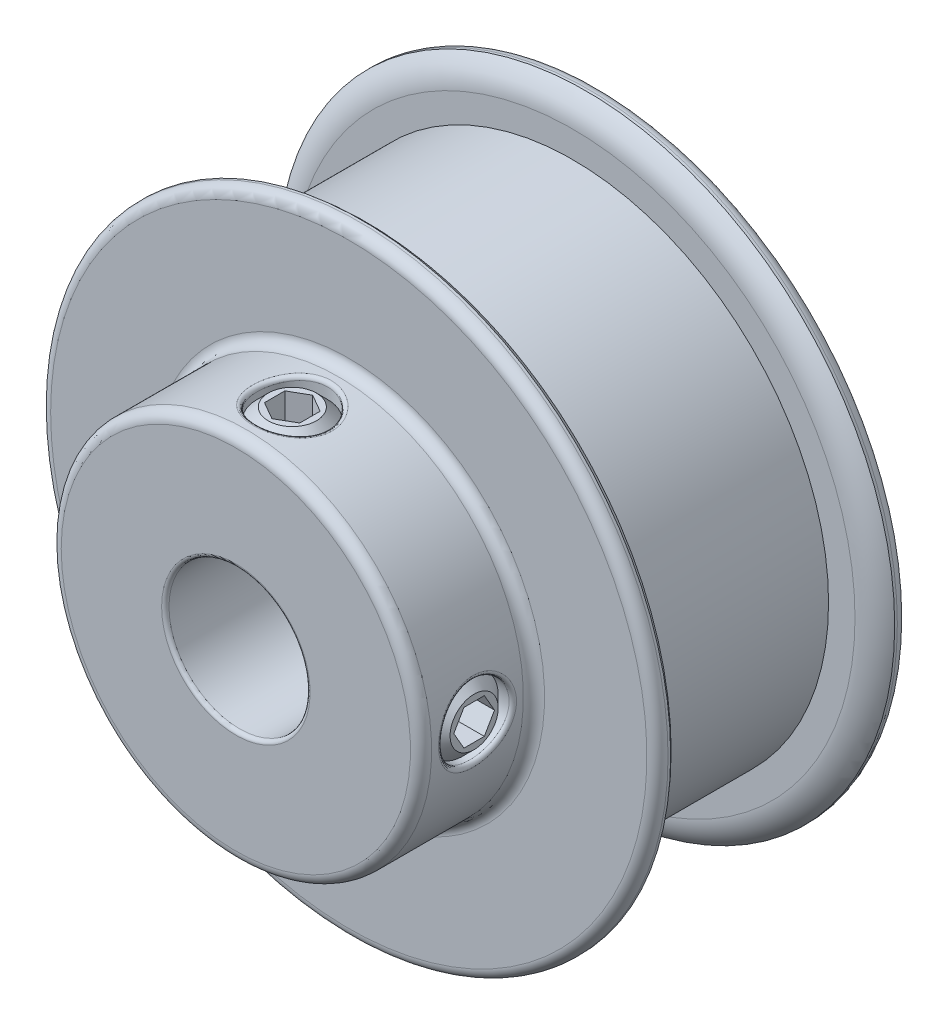
SolidWorks part; units mm, degrees
ref_plane "Front Plane" through (0, 0, 0) normal (0, 0, 1) x (1, 0, 0)
ref_plane "Top Plane" through (0, 0, 0) normal (0, 1, 0) x (1, 0, 0)
ref_plane "Right Plane" through (0, 0, 0) normal (1, 0, 0) x (0, 0, -1)
sketch "Sketch1" plane through (0, 0, 0) normal (0, 0, 1) x (1, 0, 0)
  line L0 (-1.2827, 14.4434) -> (-0.6905, 13.1734)
  line L1 (-0.6905, 13.1734) -> (0.6905, 13.1734)
  line L2 (0.6905, 13.1734) -> (1.2827, 14.4434)
  line L3 (-1.2827, 14.4434) -> (1.2827, 14.4434)
  line L4 (0, 0) -> (0, 13.1734) construction
  line L5 (0, 13.1734) -> (0, 15.4594) construction
  circle A0 centre (0, 0) radius 14.55 construction
  circle A1 centre (0, 0) radius 17.5 construction
  circle A2 centre (0, 0) radius 14.5002 construction
  point P6 (0, 14.4434)
  point P11 (0, 14.55)
  point P13 (0, 17.5)
  point P14 (0, 14.5002)
  dimension "Pitch Diameter" = 29.1
  dimension "OD" = 35
  dimension "D5" = 50
  dimension "D6" = 2.5654
  dimension "D4" = 1.27
  dimension "D3" = 2.286
  dimension "D2" = 0.9094
sketch "Sketch2" plane through (0, 0, 0) normal (1, 0, 0) x (0, 0, -1)
  line L0 (-10.3, 4) -> (10.3, 4) construction
  line L1 (-10.3, 4) -> (-10.3, 10.5) construction
  line L2 (-10.3, 10.5) -> (-3.9, 10.5) construction
  line L3 (-3.9, 10.5) -> (-3.9, 17.5) construction
  line L4 (-3.9, 17.5) -> (-2.4, 17.5) construction
  line L5 (-2.4, 17.5) -> (-2.4, 14.5002) construction
  line L6 (-2.4, 14.5002) -> (8.8, 14.5002) construction
  line L7 (8.8, 14.5002) -> (8.8, 17.5) construction
  line L8 (8.8, 17.5) -> (10.3, 17.5) construction
  line L9 (10.3, 17.5) -> (10.3, 4) construction
  line L10 (-10.3, 0) -> (10.3, 0) construction
  line L13 (-3.9, 17.5) -> (-3.15, 17.5) construction
  line L14 (-2.4, 16.0001) -> (-2.4, 14.5002) construction
  line L15 (8.8, 14.5002) -> (8.8, 16.0001) construction
  line L16 (9.55, 17.5) -> (10.3, 17.5) construction
  arc A0 (-2.4, 16.0001) -> (-3.15, 17.5) centre (-4.2748, 16.0001) ccw construction
  arc A1 (8.8, 16.0001) -> (9.55, 17.5) centre (10.6748, 16.0001) cw construction
  point P12 (-2.4, 16.0001)
  point P14 (-3.15, 17.5)
  point P20 (8.8, 16.0001)
  point P21 (9.55, 17.5)
  point P25 (8.8, 0)
  point P26 (-2.4, 0)
  dimension "Overall Width" = 20.6
  dimension "Outside Width" = 14.2
  dimension "Inside Width" = 11.2
  dimension "Hub Diameter" = 21
  dimension "For Shaft Diameter" = 8
sketch "Sketch7" plane through (0, 0, 0) normal (1, 0, 0) x (0, 0, -1)
  line L0 (-10.3, 4) -> (-10.3, 10.5) construction
  line L1 (-10.3, 10.5) -> (-3.9, 10.5) construction
  line L2 (-3.9, 10.5) -> (-3.9, 17.5) construction
  line L3 (-3.9, 17.5) -> (-3.15, 17.5) construction
  line L4 (-2.4, 16.0001) -> (-2.4, 14.5002) construction
  line L5 (-2.4, 14.5002) -> (8.8, 14.5002) construction
  line L6 (8.8, 14.5002) -> (8.8, 16.0001) construction
  line L7 (9.55, 17.5) -> (10.3, 17.5) construction
  line L8 (10.3, 17.5) -> (10.3, 4) construction
  line L9 (-10.3, 4) -> (10.3, 4) construction
  line L10 (-10.3, 4) -> (-10.3, 10.5)
  line L11 (-10.3, 10.5) -> (-3.9, 10.5)
  line L12 (-3.9, 10.5) -> (-3.9, 17.5)
  line L13 (-3.9, 17.5) -> (-3.15, 17.5)
  line L14 (-2.4, 16.0001) -> (-2.4, 14.5002)
  line L15 (-2.4, 14.5002) -> (8.8, 14.5002)
  line L16 (8.8, 14.5002) -> (8.8, 16.0001)
  line L17 (9.55, 17.5) -> (10.3, 17.5)
  line L18 (10.3, 17.5) -> (10.3, 4)
  line L19 (-10.3, 4) -> (10.3, 4)
  arc A0 (-2.4, 16.0001) -> (-3.15, 17.5) centre (-4.2748, 16.0001) ccw construction
  arc A1 (9.55, 17.5) -> (8.8, 16.0001) centre (10.6748, 16.0001) ccw construction
  arc A2 (-2.4, 16.0001) -> (-3.15, 17.5) centre (-4.2748, 16.0001) ccw
  arc A3 (9.55, 17.5) -> (8.8, 16.0001) centre (10.6748, 16.0001) ccw
revolve "Revolve1" add sketch "Sketch7" angle 360 about L10
sketch "Sketch4" plane through (0, 0, 0) normal (0, 1, 0) x (1, 0, 0)
  line L0 (0, -3.9) -> (0, -10.3) construction
  line L3 (0, -10.3) -> (0, 10.3) construction
  line L4 (-10.5, -3.9) -> (10.5, -3.9) construction
  line L5 (-10.5, -10.3) -> (10.5, -10.3) construction
  circle A0 centre (0, -7.1) radius 2
  dimension "D1" = 4
extrude "Cut-Extrude2" cut sketch "Sketch4" along normal through all
ref_plane "Plane1" through (0, 0, 7.1) normal (0, 0, 1) x (1, 0, 0)
sketch "Sketch5" plane through (0, 0, 7.1) normal (0, 0, 1) x (1, 0, 0)
  line L0 (0, 0) -> (0, 10.5) construction
  line L1 (-2, 10.3078) -> (-2, 3.4641) construction
  line L2 (-2, 10.3078) -> (-2, 3.4641) construction
  line L3 (0, 10.3078) -> (0, 4)
  line L4 (0, 4) -> (-1.365, 4)
  line L5 (-2, 9.6728) -> (-2, 4.635)
  line L6 (-1.365, 10.3078) -> (0, 10.3078)
  line L7 (-2, 9.6728) -> (-1.365, 10.3078)
  line L8 (-2, 4.635) -> (-1.365, 4)
  line L9 (0, 17.5) -> (0, 4) construction
  line L10 (0, 4) -> (0, 10.5) construction
  point P13 (-2, 4)
  point P15 (-2, 10.3078)
revolve "Revolve2" add sketch "Sketch5" angle 360 mid plane about L0
sketch "Sketch6" plane through (0, 10.3078, 0) normal (0, -1, 0) x (-1, 0, 0)
  line L1 (0, -5.9453) -> (-1, -6.5226)
  line L2 (-1, -6.5226) -> (-1, -7.6774)
  line L3 (-1, -7.6774) -> (0, -8.2547)
  line L4 (0, -8.2547) -> (1, -7.6774)
  line L5 (1, -7.6774) -> (1, -6.5226)
  line L6 (1, -6.5226) -> (0, -5.9453)
  circle A0 centre (0, -7.1) radius 1 construction
  dimension "D1" = 2
extrude "Cut-Extrude3" cut sketch "Sketch6" along normal blind 1.5
pattern_circular "CirPattern2" count 2 every 90 about axis through (0, 0, 0) along (0, 0, 1) of "Cut-Extrude2", "Revolve2", "Cut-Extrude3"
fillet "Fillet1" radius 0.6 4 edges at (17.5, 0, -10.3) (17.5, 0, 3.9) (10.5, 0, 3.9) (10.5, 0, 10.3)
fillet "Fillet2" radius 0.21 4 edges at (4, 0, 10.3) (10.4916, -0.4196, 9.0555) (0.4196, 10.4916, 9.0555) (4, 0, -10.3)
equation "\"D1@Sketch4\" = \"For Shaft Diameter@Sketch2\"/2"
equation "\"D1@Sketch6\" = \"D1@Sketch4\"/2"
equation "\"D1@Cut-Extrude3\" = \"D1@Sketch6\"*.75"
equation "\"D1@Fillet1\"=\"Hub Diameter@Sketch2\" / 35"
equation "\"D2@Sketch1\"=\"Pitch Diameter@Sketch1\"/32"
equation "\"D1@Fillet2\"=\"Hub Diameter@Sketch2\"*.01"
